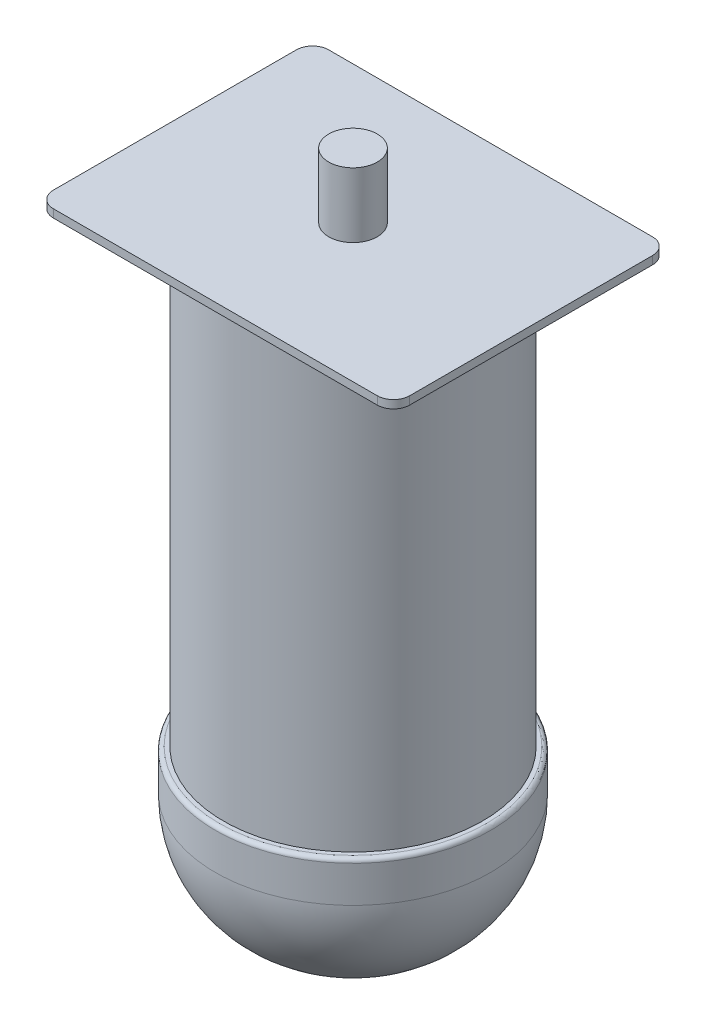
SolidWorks part; units mm, degrees
ref_plane "Plan de face" through (0, 0, 0) normal (0, 0, 1) x (1, 0, 0)
ref_plane "Plan de dessus" through (0, 0, 0) normal (0, 1, 0) x (1, 0, 0)
ref_plane "Plan de droite" through (0, 0, 0) normal (1, 0, 0) x (0, 0, -1)
sketch "Esquisse1" plane through (0, 0, 0) normal (0, 1, 0) x (1, 0, 0)
  line L1 (2, 0) -> (42, 0)
  line L2 (0, 2) -> (0, 32)
  line L3 (2, 34) -> (42, 34)
  line L4 (44, 2) -> (44, 32)
  arc A0 (42, 34) -> (44, 32) centre (42, 32) cw
  arc A1 (42, 0) -> (44, 2) centre (42, 2) ccw
  arc A2 (2, 0) -> (0, 2) centre (2, 2) cw
  arc A3 (0, 32) -> (2, 34) centre (2, 32) cw
  point P11 (0, 0)
  dimension "D3" = 2
  dimension "D1" = 44
  dimension "D2" = 34
extrude "Boss.-Extru.1" add sketch "Esquisse1" along normal blind 1
sketch "Esquisse2" plane through (0, 0, 0) normal (0, -1, 0) x (1, 0, 0)
  line L0 (0, -17) -> (44, -17) construction
  line L1 (0, -32) -> (0, -2) construction
  line L2 (44, -2) -> (44, -32) construction
  circle A0 centre (22, -17) radius 16
  dimension "D1" = 32
extrude "Boss.-Extru.2" add sketch "Esquisse2" along normal blind 55
sketch "Esquisse3" plane through (0, -55, 0) normal (0, -1, 0) x (1, 0, 0)
  circle A0 centre (22, -17) radius 17
  circle A1 centre (22, -17) radius 16 construction
  dimension "D1" = 34
extrude "Boss.-Extru.3" add sketch "Esquisse3" along normal blind 20
fillet "Congé1" radius 15 1 edges at (22, -75, -34)
fillet "Congé2" radius 0.5 1 edges at (22, -55, -34)
sketch "Esquisse4" plane through (0, 1, 0) normal (0, 1, 0) x (1, 0, 0)
  line L0 (0, 17) -> (44, 17) construction
  line L1 (0, 32) -> (0, 2) construction
  line L2 (44, 2) -> (44, 32) construction
  circle A0 centre (22, 17) radius 3
  dimension "D1" = 6
extrude "Boss.-Extru.4" add sketch "Esquisse4" along normal blind 8
ref_plane "Plan1" through (0, 0, -17) normal (0, 0, 1) x (1, 0, 0)
